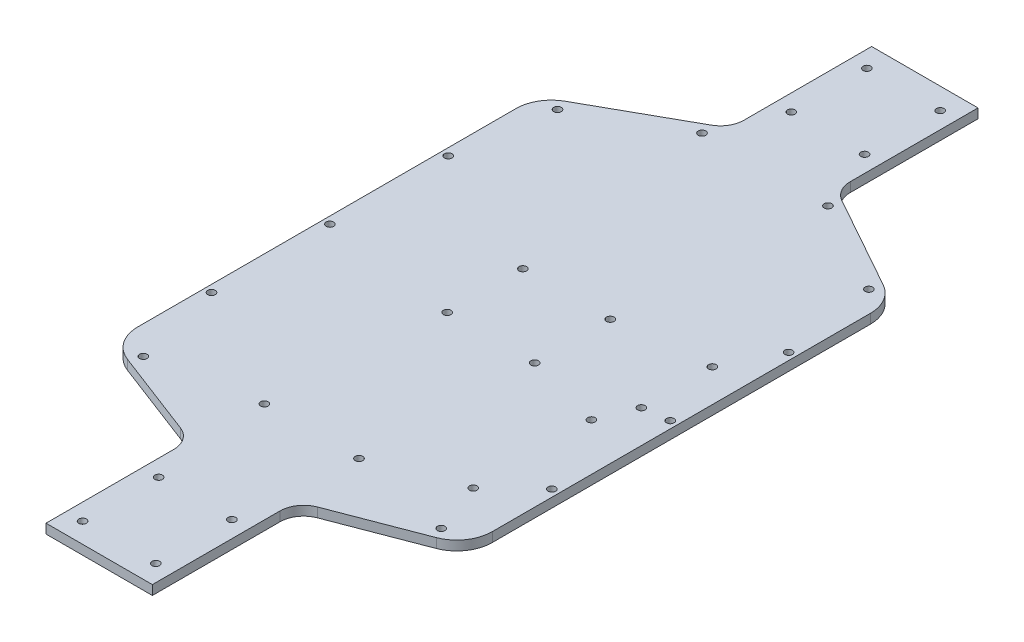
SolidWorks part; units mm, degrees
material "Thornel Mat VMA"
ref_plane "Plan de face" through (0, 0, 0) normal (0, 0, 1) x (1, 0, 0)
ref_plane "Plan de dessus" through (0, 0, 0) normal (0, 1, 0) x (1, 0, 0)
ref_plane "Plan de droite" through (0, 0, 0) normal (1, 0, 0) x (0, 0, -1)
sketch "Esquisse1" plane through (0, 0, 0) normal (0, -1, 0) x (1, 0, 0)
  line L0 (22.5, 171.3) -> (22.5, 117.3)
  line L1 (28.9241, 107.9612) -> (65.3638, 94.0082)
  line L2 (75, 80) -> (75, -80)
  line L3 (67.3157, -93.095) -> (27.6229, -115.27)
  line L4 (22.5, -124) -> (22.5, -178)
  line L14 (22.5, 171.3) -> (-22.5, 171.3)
  line L18 (0, 171.3) -> (0, -178) construction
  line L20 (-22.5, -178) -> (22.5, -178)
  line L22 (-22.5, -124) -> (-22.5, -178)
  line L23 (-67.3157, -93.095) -> (-27.6229, -115.27)
  line L25 (-75, 80) -> (-75, -80)
  line L26 (-28.9241, 107.9612) -> (-65.3638, 94.0082)
  line L27 (-22.5, 171.3) -> (-22.5, 117.3)
  arc A0 (28.9241, 107.9612) -> (22.5, 117.3) centre (32.5, 117.3) cw
  arc A1 (65.3638, 94.0082) -> (75, 80) centre (60, 80) cw
  arc A2 (75, -80) -> (67.3157, -93.095) centre (60, -80) cw
  arc A3 (22.5, -124) -> (27.6229, -115.27) centre (32.5, -124) cw
  arc A12 (-22.5, -124) -> (-27.6229, -115.27) centre (-32.5, -124) ccw
  arc A13 (-75, -80) -> (-67.3157, -93.095) centre (-60, -80) ccw
  arc A14 (-65.3638, 94.0082) -> (-75, 80) centre (-60, 80) ccw
  arc A15 (-28.9241, 107.9612) -> (-22.5, 117.3) centre (-32.5, 117.3) ccw
  point P18 (0, -178)
  point P19 (0, 171.3)
  point P36 (-75, 0)
  dimension "D7" = 15
  dimension "D8" = 10
  dimension "D1" = 150
  dimension "D2" = 45
  dimension "D3" = 349.3
  dimension "D4" = 54
  dimension "D5" = 54
  dimension "D6" = 44
  dimension "D9" = 178
  dimension "D10" = 75
extrude "Boss.-Extru.1" add sketch "Esquisse1" along normal blind 4
hole_wizard "Fraisage pour vis à tête fraisée M31" positions "Esquisse3" profile "Esquisse2" countersink size "M3" standard "Ansi Metric" end condition up to next
sketch "Esquisse3" plane through (0, -4, 0) normal (0, -1, 0) x (-1, 0, 0)
  line L0 (-75, 80) -> (-75, -80) construction
  line L1 (22.5, 124) -> (22.5, 178) construction
  line L2 (22.5, 178) -> (-22.5, 178) construction
  line L3 (-22.5, 178) -> (-22.5, 124) construction
  line L4 (-75, 80) -> (-75, -80) construction
  point P0 (14.85, -9.22)
  point P3 (-22.15, -9.22)
  point P6 (-61.15, -3.06)
  point P9 (-61.15, 26.94)
  point P12 (-22.15, 22.78)
  point P15 (14.85, 22.78)
  point P18 (15.5, 137)
  point P21 (-15.5, 137)
  point P24 (15.5, 169)
  point P27 (-15.5, 169)
  point P30 (63.0257, -89.6123)
  point P32 (72, -51.7763)
  point P34 (72, 48.3763)
  point P36 (65.8526, 88.476)
  point P38 (26.643, 110.381)
  point P40 (-26.643, 110.381)
  point P42 (-65.8526, 88.476)
  point P44 (-72, 48.3763)
  point P46 (-63.0257, -89.6123)
  point P48 (-72, -51.7763)
  point P49 (20, -81.3983)
  point P51 (-20, -81.3983)
  point P59 (-72, -1.7)
  point P61 (72, -1.7)
  point P67 (-55, -68.06)
  point P71 (-55, -18.06)
  dimension "D1" = 13.85
  dimension "D2" = 15
  dimension "D3" = 30
  dimension "D4" = 32
  dimension "D5" = 37
  dimension "D6" = 39
  dimension "D7" = 6.16
  dimension "D8" = 7
  dimension "D9" = 32
  dimension "D10" = 9
  dimension "D11" = 7
  dimension "D12" = 22.78
  dimension "D13" = 50
  dimension "D14" = 20
sketch "Esquisse2" plane through (-14.85, -4, 9.22) normal (1, 0, 0) x (0, 0, -1)
  line L0 (0, 0) -> (0, 4)
  line L1 (0, 4) -> (1.6, 4)
  line L2 (1.6, 4) -> (1.6, 1.7)
  line L3 (1.6, 1.7) -> (2.9, 0.4)
  line L4 (2.9, 0.4) -> (2.9, 0)
  line L6 (2.9, 0) -> (0, 0)
  line L7 (-1.6, 1.7) -> (-2.9, 0.4) construction
  line L11 (0, -6.35) -> (0, 107.95) construction
  dimension "Diamètre du perçage jusqu'au prochain" = 3.2
  dimension "Profondeur du perçage jusqu'au prochain" = 4
  dimension "Diamètre du fraisage" = 5.8
  dimension "Angle du fraisage" = 90
  dimension "Dégagement de la tête" = 0.4
ref_plane "Plan1" through (15.5, 0, 0) normal (1, 0, 0) x (0, 0, -1)
sketch "Esquisse4" plane through (15.5, 0, 0) normal (1, 0, 0) x (0, 0, -1)
  line L0 (-130.4423, 1.9719) -> (-128.8511, 1.8047)
  line L1 (-133.8804, -2.9959) -> (-128.1122, -3.6022) construction
  line L2 (-128.8511, 1.8047) -> (-129.2692, -2.1734)
  line L3 (-129.2692, -2.1734) -> (-128.1122, -3.6022)
  line L4 (-128.1122, -3.6022) -> (-128.2177, -4.6063)
  line L5 (-133.9223, -3.3937) -> (-128.154, -4) construction
  line L6 (-130.4423, 1.9719) -> (-131.1019, -4.3031)
  line L7 (-131.1019, -4.3031) -> (-128.2177, -4.6063)
  line L8 (-171.3, -4) -> (-171.3, 0) construction
  line L10 (-131.1019, -4.3031) -> (-133.986, -4) construction
  line L12 (-117.3, -4) -> (-171.3, -4) construction
  line L13 (-133.986, -4) -> (-133.8804, -2.9959) construction
  line L14 (-133.8804, -2.9959) -> (-130.6932, -0.4149) construction
  line L15 (-129.2692, -2.1734) -> (-130.6932, -0.4149) construction
  point P19 (-131.07, -4)
  dimension "D1" = 90
  dimension "D2" = 5.8
  dimension "D3" = 0.4
  dimension "D4" = 1.6
  dimension "D5" = 4
  dimension "D6" = 84
  dimension "D7" = 40.23
revolve "Enlèvement de matière-Révolution1" cut sketch "Esquisse4" angle 360 about L6
sketch "Esquisse6" plane through (15.5, 0, 0) normal (1, 0, 0) x (0, 0, -1)
  line L0 (-162.8258, 0) -> (-163.2463, -4) construction
  line L1 (-117.3, -4) -> (-171.3, -4) construction
  line L2 (-117.3, 0) -> (-171.3, 0) construction
  line L5 (-130.6496, 0) -> (-131.07, -4) construction
  dimension "D1" = 84
  dimension "D2" = 32
sketch "Esquisse5" plane through (15.5, 0, 0) normal (1, 0, 0) x (0, 0, -1)
  line L0 (-162.7555, 0.6689) -> (-161.1643, 0.5017)
  line L1 (-161.1643, 0.5017) -> (-161.4453, -2.1714)
  line L2 (-161.4453, -2.1714) -> (-160.2849, -3.6026)
  line L3 (-160.2849, -3.6026) -> (-160.3302, -4)
  line L4 (-160.3302, -4) -> (-160.3993, -4.6063)
  line L5 (-160.3993, -4.6063) -> (-163.2782, -4.3037)
  line L6 (-163.2782, -4.3037) -> (-166.1677, -4) construction
  line L7 (-166.1677, -4) -> (-166.0986, -3.3937) construction
  line L8 (-166.0533, -2.9963) -> (-162.8694, -0.4148) construction
  line L9 (-162.7555, 0.6689) -> (-163.2782, -4.3037)
  line L10 (-166.0986, -3.3937) -> (-166.0533, -2.9963) construction
  line L11 (-160.3302, -4) -> (-166.0986, -3.3937) construction
  line L12 (-162.8258, 0) -> (-163.2463, -4) construction
  line L13 (-171.3, -4) -> (-117.3, -4) construction
  line L14 (-157.2606, -6.1647) -> (-155.7772, 6.8554) construction
  line L16 (-117.3, -4) -> (-171.3, -4) construction
  line L17 (-161.4453, -2.1714) -> (-162.8694, -0.4148) construction
  point P11 (-163.2144, -3.6969)
  point P20 (-163.2463, -4)
  dimension "D1" = 5.8
  dimension "D2" = 0.4
  dimension "D3" = 90
  dimension "D4" = 1.6
  dimension "D6" = 5
revolve "Enlèvement de matière-Révolution2" cut sketch "Esquisse5" angle 360 about L9
mirror "Symétrie1" about plane through (0, 0, 0) normal (1, 0, 0) of "Enlèvement de matière-Révolution2", "Enlèvement de matière-Révolution1"
